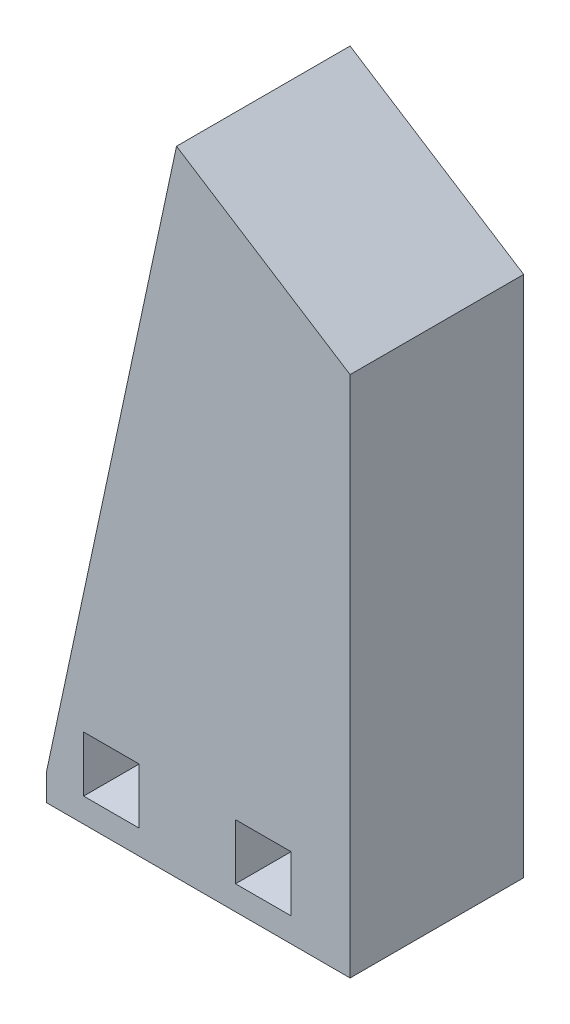
SolidWorks part; units mm, degrees
material "ABS"
ref_plane "前视基准面" through (0, 0, 0) normal (0, 0, 1) x (1, 0, 0)
ref_plane "上视基准面" through (0, 0, 0) normal (0, 1, 0) x (1, 0, 0)
ref_plane "右视基准面" through (0, 0, 0) normal (1, 0, 0) x (0, 0, -1)
other "Configuration Table"
sketch "草图3" plane through (0, 0, 0) normal (0, 0, 1) x (1, 0, 0)
  line L0 (67.1123, -42.9201) -> (77.8877, -26.0711) construction
  line L1 (0, 0) -> (20, -12.7905)
  line L2 (0, 0) -> (0, -72.9956)
  line L3 (0, -72.9956) -> (20, -72.9956)
  line L4 (20, -12.7905) -> (20, -72.9956)
  line L5 (67.1123, -42.9201) -> (-18.1166, 11.5861) construction
  line L6 (77.8877, -26.0711) -> (-7.3412, 28.4351) construction
  line L7 (-18.1166, 11.5861) -> (-7.3412, 28.4351) construction
  circle A0 centre (72.5, -34.4956) radius 10 construction
  point P7 (72.5, -9.0736)
  point P10 (72.5, -12.7905)
  dimension "D6" = 20
  dimension "D1" = 20
  dimension "D3" = 32.6
  dimension "D4" = 52.5
  dimension "D5" = 38.5
extrude "凸台-拉伸1" add sketch "草图3" along normal blind 20
sketch "草图6" plane through (0, 0, 20) normal (0, 0, 1) x (1, 0, 0)
  line L0 (0, -72.9956) -> (-15, -72.9956)
  line L1 (-15, -72.9956) -> (-15, -69.9956)
  line L2 (-15, -69.9956) -> (0, 0)
  line L3 (0, 0) -> (0, -69.9956)
  line L4 (0, 0) -> (0, -72.9956) construction
  line L7 (0, -69.9956) -> (0, -72.9956)
  point P3 (0, -69.5139)
  point P7 (-15, -67.9285)
  dimension "D1" = 3
  dimension "D3" = 15
extrude "凸台-拉伸2" add sketch "草图6" against normal up to surface (20 mm away) up to face at (10, -39.6954, 0)
sketch "草图11" plane through (0, 0, 20) normal (0, 0, 1) x (1, 0, 0)
  line L0 (-7.5, -1055.8884) -> (-7.5, 48944.1116) construction
  line L1 (10, -1056.428) -> (10, 48943.572) construction
  line L2 (-15, -69.9956) -> (-15, -72.9956) construction
  line L3 (20, -72.9956) -> (20, -12.7905) construction
  line L4 (-7.5, -66.9956) -> (10, -66.9956) construction
  line L5 (-10.5, -63.9956) -> (-4.5, -63.9956) construction
  line L6 (-10.5, -63.9956) -> (-10.5, -69.9956) construction
  line L7 (-10.5, -69.9956) -> (-4.5, -69.9956) construction
  line L8 (-4.5, -63.9956) -> (-4.5, -69.9956) construction
  line L9 (-10.5, -63.9956) -> (-4.5, -69.9956) construction
  line L10 (-10.5, -69.9956) -> (-4.5, -63.9956) construction
  line L11 (7, -63.9956) -> (13, -63.9956) construction
  line L12 (7, -63.9956) -> (7, -69.9956) construction
  line L13 (7, -69.9956) -> (13, -69.9956) construction
  line L14 (13, -63.9956) -> (13, -69.9956) construction
  line L15 (7, -63.9956) -> (13, -69.9956) construction
  line L16 (7, -69.9956) -> (13, -63.9956) construction
  line L17 (-15, -72.9956) -> (20, -72.9956) construction
  line L18 (-10.7, -63.7956) -> (-10.7, -70.1956)
  line L19 (-10.7, -70.1956) -> (-4.3, -70.1956)
  line L20 (-4.3, -63.7956) -> (-4.3, -70.1956)
  line L21 (-10.7, -63.7956) -> (-4.3, -63.7956)
  line L22 (6.8, -63.7956) -> (6.8, -70.1956)
  line L23 (6.8, -70.1956) -> (13.2, -70.1956)
  line L24 (13.2, -63.7956) -> (13.2, -70.1956)
  line L25 (6.8, -63.7956) -> (13.2, -63.7956)
  point P8 (-7.5, -66.9956)
  point P13 (10, -66.9956)
  dimension "D1" = 7.5
  dimension "D2" = 10
  dimension "D3" = 6
  dimension "D4" = 3
  dimension "D5" = 0.2
  dimension "D6" = 0.2
extrude "切除-拉伸2" cut sketch "草图11" against normal offset from surface (13.1 mm away) 6.9 up to face at (2, -45.7555, 0)
sketch "草图4" plane through (0, -72.9956, 0) normal (0, -1, 0) x (1, 0, 0)
  line L0 (-15, 10) -> (20, 10) construction
  line L2 (20, 20) -> (20, 0) construction
  line L3 (-15, 0) -> (-15, 20) construction
  circle A0 centre (10, 10) radius 1.6
  circle A1 centre (-7.5, 10) radius 1.6
  dimension "D1" = 3.2
  dimension "D2" = 17.5
  dimension "D3" = 10
extrude "切除-拉伸1" cut sketch "草图4" against normal up to surface (9.2 mm away) up to face at (-7.5, -63.7956, 13.45)
